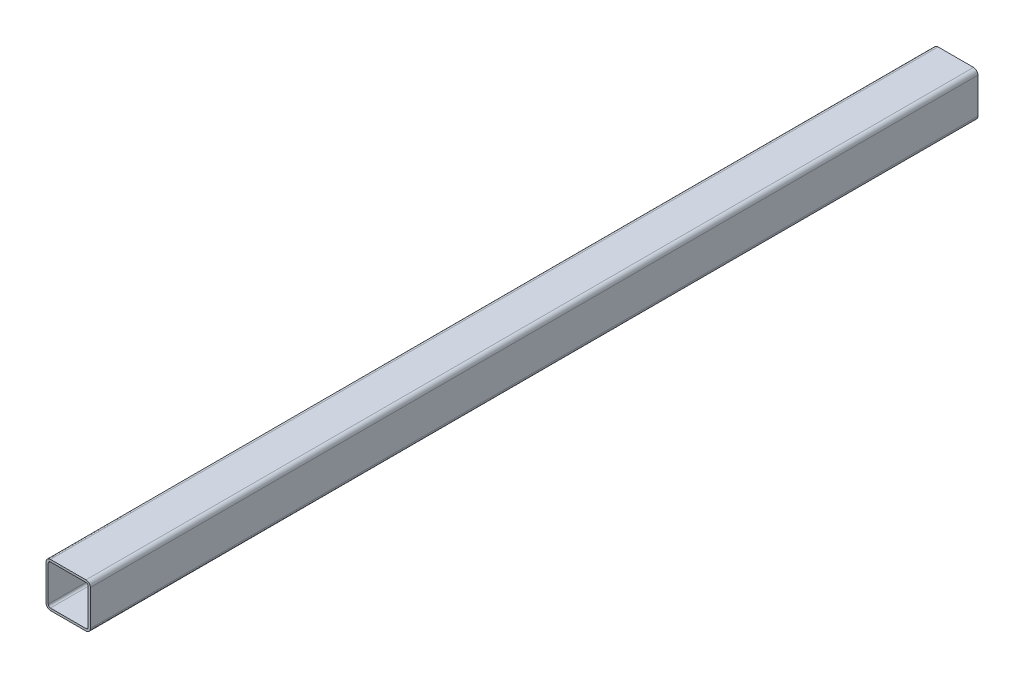
SolidWorks part; units mm, degrees
material "S355 verification"
ref_plane "Front Plane" through (0, 0, 0) normal (0, 0, 1) x (1, 0, 0)
ref_plane "Top Plane" through (0, 0, 0) normal (0, 1, 0) x (1, 0, 0)
ref_plane "Right Plane" through (0, 0, 0) normal (1, 0, 0) x (0, 0, -1)
sketch "Sketch1" plane through (0, 0, 0) normal (0, 1, 0) x (1, 0, 0)
  line L0 (0, 0) -> (0, -2000)
other "SHS100x100x5 (1)"
ref_plane "Plane1" through (0, 0, 0) normal (0, 0, 1) x (1, 0, 0)
sketch "Sketch11" plane through (0, 0, 0) normal (0, 0, 1) x (1, 0, 0)
  line L0 (-40, -50) -> (40, -50)
  line L1 (50, -40) -> (50, 40)
  line L2 (40, 50) -> (-40, 50)
  line L3 (-50, 40) -> (-50, -40)
  line L4 (-40, -45) -> (40, -45)
  line L5 (45, -40) -> (45, 40)
  line L6 (40, 45) -> (-40, 45)
  line L7 (-45, 40) -> (-45, -40)
  arc A0 (40, -50) -> (50, -40) centre (40, -40) ccw
  arc A1 (50, 40) -> (40, 50) centre (40, 40) ccw
  arc A2 (-40, 50) -> (-50, 40) centre (-40, 40) ccw
  arc A3 (-50, -40) -> (-40, -50) centre (-40, -40) ccw
  arc A4 (40, -45) -> (45, -40) centre (40, -40) ccw
  arc A5 (45, 40) -> (40, 45) centre (40, 40) ccw
  arc A6 (-40, 45) -> (-45, 40) centre (-40, 40) ccw
  arc A7 (-45, -40) -> (-40, -45) centre (-40, -40) ccw
  point P20 (0, 0)
